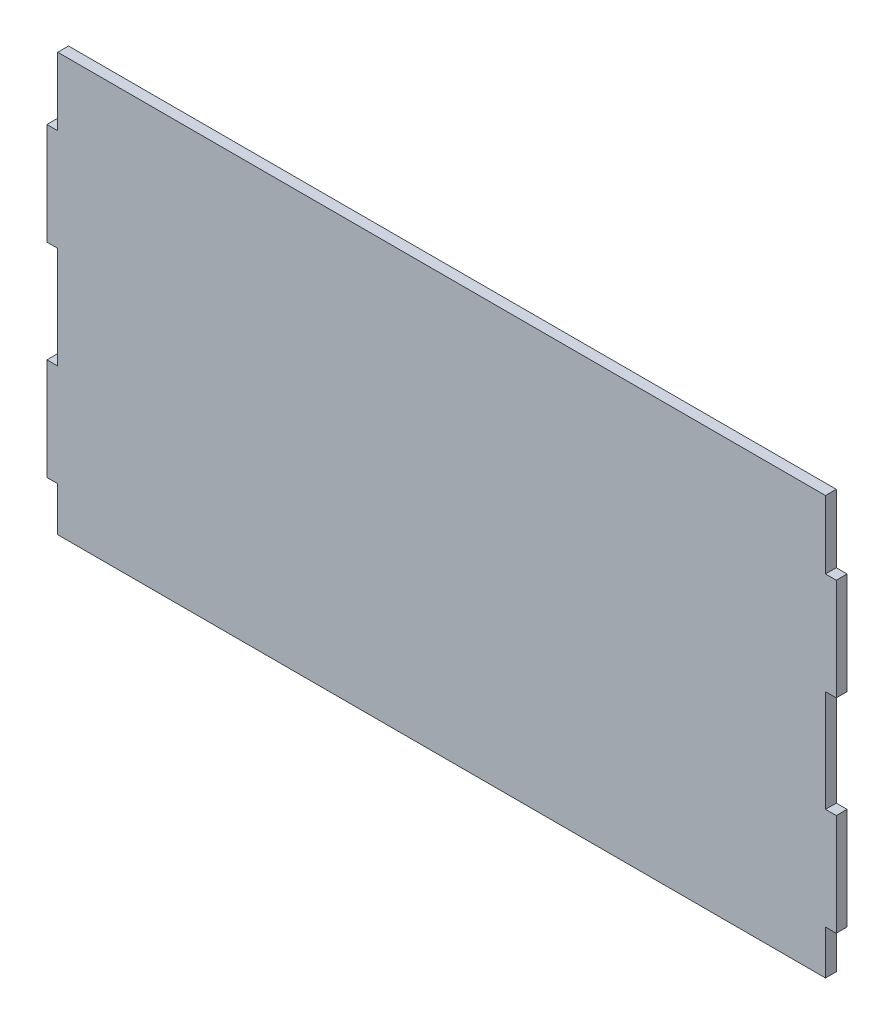
SolidWorks part; units mm, degrees
ref_plane "前视" through (0, 0, 0) normal (0, 0, 1) x (1, 0, 0)
ref_plane "上视" through (0, 0, 0) normal (0, 1, 0) x (1, 0, 0)
ref_plane "右视" through (0, 0, 0) normal (1, 0, 0) x (0, 0, -1)
sketch "Sketch1" plane through (0, 0, 0) normal (0, 0, 1) x (1, 0, 0)
  line L1 (0, 0) -> (226, 0)
  line L2 (0, 0) -> (0, -123)
  line L3 (0, -123) -> (226, -123)
  line L4 (226, 0) -> (226, -123)
  dimension "D1" = 226
  dimension "D2" = 123
extrude "Boss-Extrude1" add sketch "Sketch1" along normal blind 3.175
sketch "Sketch2" plane through (0, 0, 3.175) normal (0, 0, 1) x (1, 0, 0)
  line L0 (0, 0) -> (0, -123) construction
  line L1 (0, -20) -> (-3.175, -20)
  line L2 (0, -20) -> (0, -50)
  line L3 (0, -50) -> (-3.175, -50)
  line L4 (-3.175, -20) -> (-3.175, -50)
  line L5 (226, 0) -> (0, 0) construction
  line L6 (226, -123) -> (226, 0) construction
  line L7 (226, -20) -> (229.175, -20)
  line L8 (226, -20) -> (226, -50)
  line L9 (226, -50) -> (229.175, -50)
  line L10 (229.175, -20) -> (229.175, -50)
  line L11 (0, -80) -> (-3.175, -80)
  line L12 (-3.175, -80) -> (-3.175, -110)
  line L13 (0, -80) -> (0, -110)
  line L14 (0, -110) -> (-3.175, -110)
  line L15 (226, -80) -> (229.175, -80)
  line L16 (229.175, -80) -> (229.175, -110)
  line L17 (226, -80) -> (226, -110)
  line L18 (226, -110) -> (229.175, -110)
  dimension "D1" = 3.175
  dimension "D2" = 20
  dimension "D3" = 30
  dimension "D4" = 3.175
  dimension "D5" = 2
extrude "Boss-Extrude2" add sketch "Sketch2" against normal up to surface (3.175 mm away) up to face at (113, -61.5, 0)
